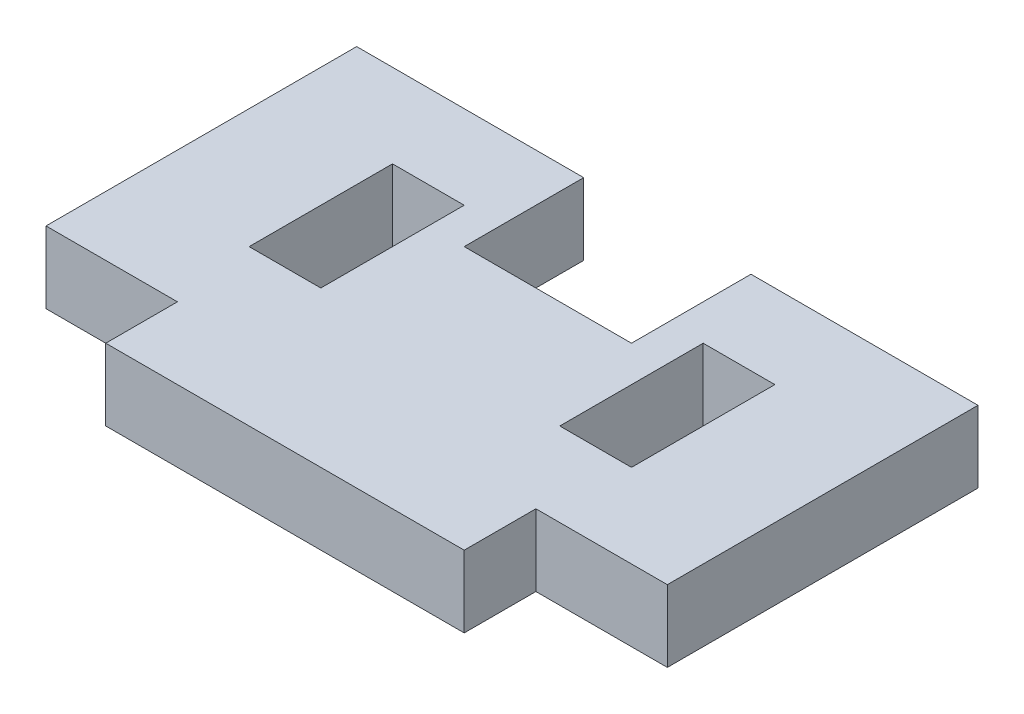
SolidWorks part; units mm, degrees
ref_plane "Alzado" through (0, 0, 0) normal (0, 0, 1) x (1, 0, 0)
ref_plane "Planta" through (0, 0, 0) normal (0, 1, 0) x (1, 0, 0)
ref_plane "Vista lateral" through (0, 0, 0) normal (1, 0, 0) x (0, 0, -1)
sketch "Croquis1" plane through (0, 0, 0) normal (0, 1, 0) x (1, 0, 0)
  line L0 (0, 0) -> (15, 0)
  line L1 (15, 0) -> (15, 3)
  line L2 (-5.5, 3) -> (0, 3)
  line L3 (20.5, 3) -> (20.5, 16)
  line L4 (20.5, 16) -> (11, 16)
  line L5 (-5.5, 3) -> (-5.5, 16)
  line L6 (0, 0) -> (0, 3)
  line L7 (15, 3) -> (20.5, 3)
  line L8 (7.5, 16) -> (7.5, 3) construction
  line L9 (7.5, 11) -> (4, 11)
  line L10 (4, 11) -> (4, 16)
  line L11 (7.5, 11) -> (11, 11)
  line L12 (11, 11) -> (11, 16)
  line L13 (7.5, 9.5) -> (-5.5, 9.5) construction
  line L14 (4, 16) -> (-5.5, 16)
  line L16 (1, 12.5) -> (2.5, 12.5)
  line L17 (2.5, 12.5) -> (2.5, 6.5)
  line L18 (2.5, 6.5) -> (-0.5, 6.5)
  line L19 (-0.5, 6.5) -> (-0.5, 12.5)
  line L20 (-0.5, 12.5) -> (1, 12.5)
  line L21 (12.5, 6.5) -> (15.5, 6.5)
  line L23 (12.5, 12.5) -> (12.5, 6.5)
  line L25 (15.5, 6.5) -> (15.5, 12.5)
  line L26 (15.5, 12.5) -> (14, 12.5)
  line L27 (14, 12.5) -> (12.5, 12.5)
  point P9 (7.5, 16)
  dimension "D1" = 15
  dimension "D3" = 3.5
  dimension "D4" = 13
  dimension "D5" = 3.5
  dimension "D7" = 1.5
  dimension "D8" = 3
extrude "Saliente-Extruir1" add sketch "Croquis1" along normal blind 3
